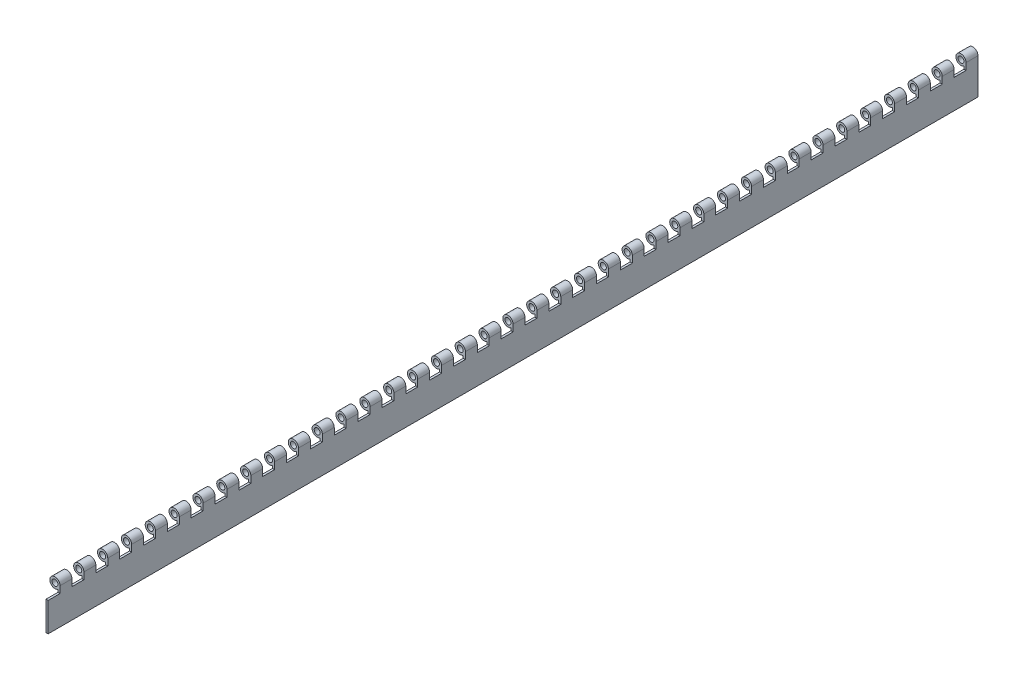
SolidWorks part; units mm, degrees
material "6061 Alloy"
ref_plane "Front Plane" through (0, 0, 0) normal (0, 0, 1) x (1, 0, 0)
ref_plane "Top Plane" through (0, 0, 0) normal (0, 1, 0) x (1, 0, 0)
ref_plane "Right Plane" through (0, 0, 0) normal (1, 0, 0) x (0, 0, -1)
sketch "Sketch1" plane through (0, 0, 0) normal (0, 0, 1) x (1, 0, 0)
  line L0 (5.461, 0) -> (5.461, -38.1)
  line L1 (5.461, -38.1) -> (3.175, -38.1)
  line L2 (3.175, -38.1) -> (3.175, -4.4432)
  circle A0 centre (0, 0) radius 3.175
  arc A1 (5.461, 0) -> (3.175, -4.4432) centre (0, 0) ccw
  circle A2 centre (0, 0) radius 5.461 construction
  dimension "D1" = 6.35
  dimension "D3" = 2.286
  dimension "D4" = 38.1
  dimension "D2" = 2.286
extrude "Boss-Extrude1" add sketch "Sketch1" along normal blind 990.6
sketch "Sketch2" plane through (5.461, 0, 0) normal (1, 0, 0) x (0, 0, -1)
  line L1 (-990.6, 5.461) -> (-977.9, 5.461)
  line L2 (-990.6, 5.461) -> (-990.6, -7.239)
  line L3 (-990.6, -7.239) -> (-977.9, -7.239)
  line L4 (-977.9, 5.461) -> (-977.9, -7.239)
  dimension "D1" = 12.7
  dimension "D2" = 12.7
extrude "Cut-Extrude1" cut sketch "Sketch2" against normal through all
pattern_linear "LPattern1" count 39 spacing 25.4 along (0, 0, -1) of "Cut-Extrude1"
